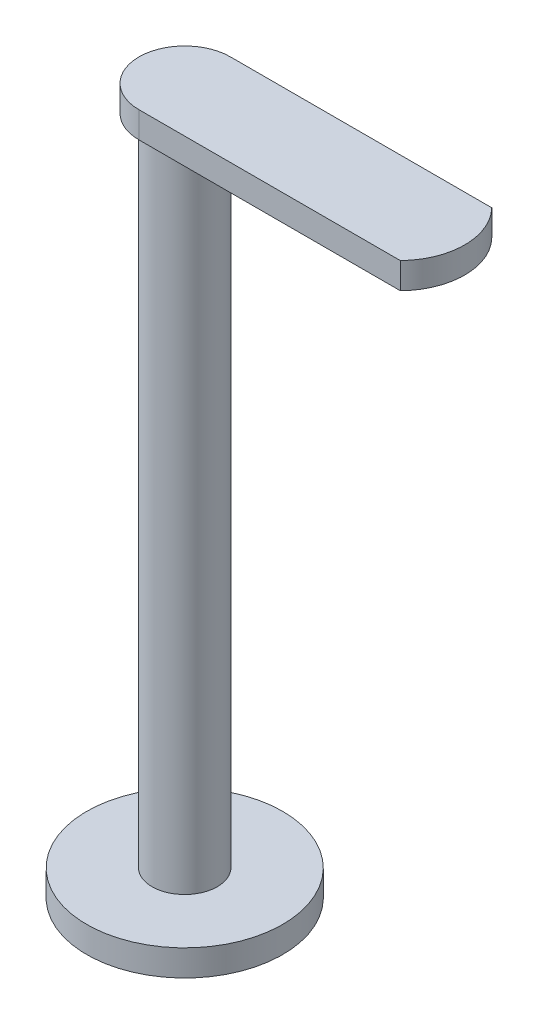
SolidWorks part; units mm, degrees
ref_plane "Front Plane" through (0, 0, 0) normal (0, 0, 1) x (1, 0, 0)
ref_plane "Top Plane" through (0, 0, 0) normal (0, 1, 0) x (1, 0, 0)
ref_plane "Right Plane" through (0, 0, 0) normal (1, 0, 0) x (0, 0, -1)
sketch "Sketch1" plane through (0, 0, 0) normal (0, 1, 0) x (1, 0, 0)
  circle A0 centre (0, 0) radius 6.35
  dimension "D1" = 12.7
extrude "Boss-Extrude2" add sketch "Sketch1" along normal blind 127
sketch "Sketch2" plane through (0, 127, 0) normal (0, 1, 0) x (1, 0, 0)
  circle A0 centre (0, 0) radius 8.89
  dimension "D1" = 17.78
extrude "Boss-Extrude3" add sketch "Sketch2" along normal blind 5.08
sketch "Sketch3" plane through (0, 132.08, 0) normal (0, 1, 0) x (1, 0, 0)
  line L1 (0, 8.89) -> (50.8, 8.89)
  line L2 (0, 8.89) -> (0, -8.89)
  line L3 (0, -8.89) -> (50.8, -8.89)
  circle A0 centre (0, 0) radius 8.89 construction
  arc A1 (50.8, 8.89) -> (50.8, -8.89) centre (41.7304, 0) cw
  dimension "D1" = 17.78
  dimension "D2" = 50.8
extrude "Boss-Extrude5" add sketch "Sketch3" against normal blind 5.08
sketch "Sketch4" plane through (0, 0, 0) normal (0, -1, 0) x (1, 0, 0)
  circle A0 centre (0, 0) radius 19.05
  dimension "D1" = 38.1
extrude "Boss-Extrude6" add sketch "Sketch4" along normal blind 5.08
